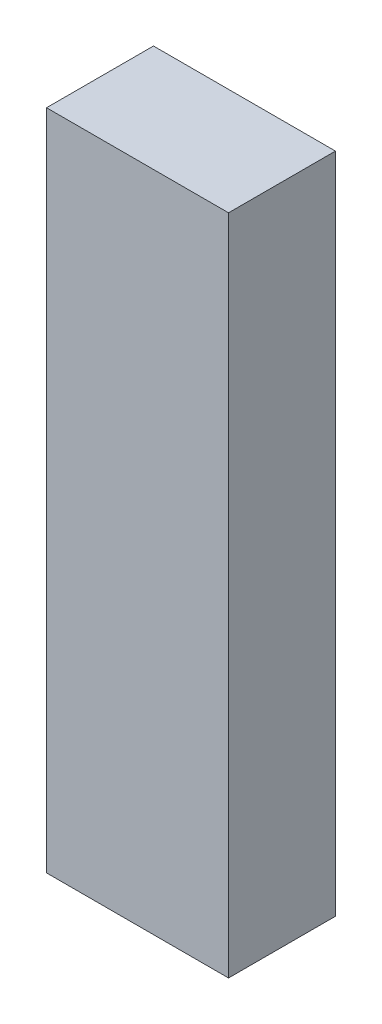
SolidWorks part; units mm, degrees
material "ABS"
ref_plane "Ground_Plane" through (0, 0, 0) normal (0, 0, 1) x (1, 0, 0)
ref_plane "VehicleCentre_Plane" through (0, 0, 0) normal (0, 1, 0) x (1, 0, 0)
ref_plane "FrontAxle_Plane" through (0, 0, 0) normal (1, 0, 0) x (0, 0, -1)
sketch "Sketch2" plane through (0, 0, 0) normal (1, 0, 0) x (0, 0, -1)
  line L1 (2.5, -15.495) -> (-2.5, -15.495)
  line L2 (2.5, -15.495) -> (2.5, 15.495)
  line L3 (2.5, 15.495) -> (-2.5, 15.495)
  line L4 (-2.5, -15.495) -> (-2.5, 15.495)
  line L5 (2.5, -15.495) -> (-2.5, 15.495) construction
  line L6 (2.5, 15.495) -> (-2.5, -15.495) construction
  point P0 (0, 0)
  dimension "D1" = 5
  dimension "D2" = 30.99
extrude "Boss-Extrude1" add sketch "Sketch2" along normal blind 8.51
sketch "Sketch3" plane through (0, 0, 0) normal (-1, 0, 0) x (0, 0, 1)
  line L0 (-2.5, -15.495) -> (-2.5, 15.495) construction
  line L1 (-1.5875, 14.2825) -> (-0.9525, 14.2825)
  line L2 (-1.5875, 14.2825) -> (-1.5875, 13.6475)
  line L3 (-1.5875, 13.6475) -> (-0.9525, 13.6475)
  line L4 (-0.9525, 14.2825) -> (-0.9525, 13.6475)
  line L5 (-1.5875, 14.2825) -> (-0.9525, 13.6475) construction
  line L6 (-1.5875, 13.6475) -> (-0.9525, 14.2825) construction
  line L7 (-2.5, 15.495) -> (2.5, 15.495) construction
  line L8 (0.9525, 14.2825) -> (0.9525, 13.6475)
  line L9 (0.9525, 14.2825) -> (1.5875, 14.2825)
  line L10 (1.5875, 14.2825) -> (1.5875, 13.6475)
  line L11 (0.9525, 13.6475) -> (1.5875, 13.6475)
  line L12 (0.9525, 11.7425) -> (0.9525, 11.1075)
  line L13 (0.9525, 11.7425) -> (1.5875, 11.7425)
  line L14 (1.5875, 11.7425) -> (1.5875, 11.1075)
  line L15 (0.9525, 11.1075) -> (1.5875, 11.1075)
  line L16 (0.9525, 9.2025) -> (0.9525, 8.5675)
  line L17 (0.9525, 9.2025) -> (1.5875, 9.2025)
  line L18 (1.5875, 9.2025) -> (1.5875, 8.5675)
  line L19 (0.9525, 8.5675) -> (1.5875, 8.5675)
  line L20 (0.9525, 6.6625) -> (0.9525, 6.0275)
  line L21 (0.9525, 6.6625) -> (1.5875, 6.6625)
  line L22 (1.5875, 6.6625) -> (1.5875, 6.0275)
  line L23 (0.9525, 6.0275) -> (1.5875, 6.0275)
  line L24 (0.9525, 4.1225) -> (0.9525, 3.4875)
  line L25 (0.9525, 4.1225) -> (1.5875, 4.1225)
  line L26 (1.5875, 4.1225) -> (1.5875, 3.4875)
  line L27 (0.9525, 3.4875) -> (1.5875, 3.4875)
  line L28 (0.9525, 1.5825) -> (0.9525, 0.9475)
  line L29 (0.9525, 1.5825) -> (1.5875, 1.5825)
  line L30 (1.5875, 1.5825) -> (1.5875, 0.9475)
  line L31 (0.9525, 0.9475) -> (1.5875, 0.9475)
  line L32 (0.9525, -0.9575) -> (0.9525, -1.5925)
  line L33 (0.9525, -0.9575) -> (1.5875, -0.9575)
  line L34 (1.5875, -0.9575) -> (1.5875, -1.5925)
  line L35 (0.9525, -1.5925) -> (1.5875, -1.5925)
  line L36 (0.9525, -3.4975) -> (0.9525, -4.1325)
  line L37 (0.9525, -3.4975) -> (1.5875, -3.4975)
  line L38 (1.5875, -3.4975) -> (1.5875, -4.1325)
  line L39 (0.9525, -4.1325) -> (1.5875, -4.1325)
  line L40 (0.9525, -6.0375) -> (0.9525, -6.6725)
  line L41 (0.9525, -6.0375) -> (1.5875, -6.0375)
  line L42 (1.5875, -6.0375) -> (1.5875, -6.6725)
  line L43 (0.9525, -6.6725) -> (1.5875, -6.6725)
  line L44 (0.9525, -8.5775) -> (0.9525, -9.2125)
  line L45 (0.9525, -8.5775) -> (1.5875, -8.5775)
  line L46 (1.5875, -8.5775) -> (1.5875, -9.2125)
  line L47 (0.9525, -9.2125) -> (1.5875, -9.2125)
  line L48 (0.9525, -11.1175) -> (0.9525, -11.7525)
  line L49 (0.9525, -11.1175) -> (1.5875, -11.1175)
  line L50 (1.5875, -11.1175) -> (1.5875, -11.7525)
  line L51 (0.9525, -11.7525) -> (1.5875, -11.7525)
  line L52 (0.9525, -13.6575) -> (0.9525, -14.2925)
  line L53 (0.9525, -13.6575) -> (1.5875, -13.6575)
  line L54 (1.5875, -13.6575) -> (1.5875, -14.2925)
  line L55 (0.9525, -14.2925) -> (1.5875, -14.2925)
  line L56 (-1.5875, 11.7425) -> (-1.5875, 11.1075)
  line L57 (-1.5875, 11.7425) -> (-0.9525, 11.7425)
  line L58 (-0.9525, 11.7425) -> (-0.9525, 11.1075)
  line L59 (-1.5875, 11.1075) -> (-0.9525, 11.1075)
  line L60 (-1.5875, 9.2025) -> (-1.5875, 8.5675)
  line L61 (-1.5875, 9.2025) -> (-0.9525, 9.2025)
  line L62 (-0.9525, 9.2025) -> (-0.9525, 8.5675)
  line L63 (-1.5875, 8.5675) -> (-0.9525, 8.5675)
  line L64 (-1.5875, 6.6625) -> (-1.5875, 6.0275)
  line L65 (-1.5875, 6.6625) -> (-0.9525, 6.6625)
  line L66 (-0.9525, 6.6625) -> (-0.9525, 6.0275)
  line L67 (-1.5875, 6.0275) -> (-0.9525, 6.0275)
  line L68 (-1.5875, 4.1225) -> (-1.5875, 3.4875)
  line L69 (-1.5875, 4.1225) -> (-0.9525, 4.1225)
  line L70 (-0.9525, 4.1225) -> (-0.9525, 3.4875)
  line L71 (-1.5875, 3.4875) -> (-0.9525, 3.4875)
  line L72 (-1.5875, 1.5825) -> (-1.5875, 0.9475)
  line L73 (-1.5875, 1.5825) -> (-0.9525, 1.5825)
  line L74 (-0.9525, 1.5825) -> (-0.9525, 0.9475)
  line L75 (-1.5875, 0.9475) -> (-0.9525, 0.9475)
  line L76 (-1.5875, -0.9575) -> (-1.5875, -1.5925)
  line L77 (-1.5875, -0.9575) -> (-0.9525, -0.9575)
  line L78 (-0.9525, -0.9575) -> (-0.9525, -1.5925)
  line L79 (-1.5875, -1.5925) -> (-0.9525, -1.5925)
  line L80 (-1.5875, -3.4975) -> (-1.5875, -4.1325)
  line L81 (-1.5875, -3.4975) -> (-0.9525, -3.4975)
  line L82 (-0.9525, -3.4975) -> (-0.9525, -4.1325)
  line L83 (-1.5875, -4.1325) -> (-0.9525, -4.1325)
  line L84 (-1.5875, -6.0375) -> (-1.5875, -6.6725)
  line L85 (-1.5875, -6.0375) -> (-0.9525, -6.0375)
  line L86 (-0.9525, -6.0375) -> (-0.9525, -6.6725)
  line L87 (-1.5875, -6.6725) -> (-0.9525, -6.6725)
  line L88 (-1.5875, -8.5775) -> (-1.5875, -9.2125)
  line L89 (-1.5875, -8.5775) -> (-0.9525, -8.5775)
  line L90 (-0.9525, -8.5775) -> (-0.9525, -9.2125)
  line L91 (-1.5875, -9.2125) -> (-0.9525, -9.2125)
  line L92 (-1.5875, -11.1175) -> (-1.5875, -11.7525)
  line L93 (-1.5875, -11.1175) -> (-0.9525, -11.1175)
  line L94 (-0.9525, -11.1175) -> (-0.9525, -11.7525)
  line L95 (-1.5875, -11.7525) -> (-0.9525, -11.7525)
  line L96 (-1.5875, -13.6575) -> (-1.5875, -14.2925)
  line L97 (-1.5875, -13.6575) -> (-0.9525, -13.6575)
  line L98 (-0.9525, -13.6575) -> (-0.9525, -14.2925)
  line L99 (-1.5875, -14.2925) -> (-0.9525, -14.2925)
  line L100 (-1.5875, 14.2825) -> (0.9525, 14.2825) construction
  line L101 (-1.5875, 14.2825) -> (-1.5875, 11.7425) construction
  point P0 (-1.27, 13.965)
  dimension "D1" = 0.635
  dimension "D2" = 1.23
  dimension "D3" = 1.53
  dimension "D6" = 2.54
  dimension "D7" = 2.54
  dimension "D4" = 2
  dimension "D5" = 12
extrude "Cut-Extrude1" cut sketch "Sketch3" against normal blind 4
chamfer "Chamfer2" distance 0.5 angle 45 96 edges at (0, 11.425, 0.9525) (0, 11.1075, 1.27) (0, 11.425, 1.5875) (0, 11.7425, 1.27) (0, 14.2825, 1.27) (0, 13.965, 1.5875) (0, 13.6475, 1.27) (0, 13.965, 0.9525) (0, 14.2825, -1.27) (0, 13.965, -1.5875) (0, 13.6475, -1.27) (0, 13.965, -0.9525) (0, 11.425, -0.9525) (0, 11.7425, -1.27) (0, 11.425, -1.5875) (0, 11.1075, -1.27) (0, 9.2025, -1.27) (0, 8.885, -1.5875) (0, 8.5675, -1.27) (0, 8.885, -0.9525) (0, 8.885, 1.5875) (0, 9.2025, 1.27) (0, 8.885, 0.9525) (0, 8.5675, 1.27) (0, 6.6625, 1.27) (0, 6.345, 1.5875) (0, 6.0275, 1.27) (0, 6.345, 0.9525) (0, 6.6625, -1.27) (0, 6.345, -1.5875) (0, 6.0275, -1.27) (0, 6.345, -0.9525) (0, 4.1225, -1.27) (0, 3.805, -1.5875) (0, 3.4875, -1.27) (0, 3.805, -0.9525) (0, 4.1225, 1.27) (0, 3.805, 0.9525) (0, 3.4875, 1.27) (0, 3.805, 1.5875) (0, 1.5825, 1.27) (0, 1.265, 1.5875) (0, 0.9475, 1.27) (0, 1.265, 0.9525) (0, 1.5825, -1.27) (0, 1.265, -1.5875) (0, 0.9475, -1.27) (0, 1.265, -0.9525) (0, -0.9575, -1.27) (0, -1.275, -0.9525) (0, -1.5925, -1.27) (0, -1.275, -1.5875) (0, -1.275, 0.9525) (0, -0.9575, 1.27) (0, -1.5925, 1.27) (0, -1.275, 1.5875) (0, -3.815, 1.5875) (0, -3.4975, 1.27) (0, -3.815, 0.9525) (0, -4.1325, 1.27) (0, -4.1325, -1.27) (0, -3.815, -1.5875) (0, -3.4975, -1.27) (0, -3.815, -0.9525) (0, -6.0375, 1.27) (0, -6.355, 1.5875) (0, -6.6725, 1.27) (0, -6.355, 0.9525) (0, -6.355, -1.5875) (0, -6.0375, -1.27) (0, -6.6725, -1.27) (0, -6.355, -0.9525) (0, -8.5775, -1.27) (0, -8.895, -1.5875) (0, -9.2125, -1.27) (0, -8.895, -0.9525) (0, -8.5775, 1.27) (0, -8.895, 0.9525) (0, -9.2125, 1.27) (0, -8.895, 1.5875) (0, -11.1175, 1.27) (0, -11.435, 1.5875) (0, -11.7525, 1.27) (0, -11.435, 0.9525) (0, -11.1175, -1.27) (0, -11.435, -0.9525) (0, -11.435, -1.5875) (0, -11.7525, -1.27) (0, -13.6575, 1.27) (0, -13.975, 1.5875) (0, -14.2925, 1.27) (0, -13.975, 0.9525) (0, -13.6575, -1.27) (0, -13.975, -1.5875) (0, -14.2925, -1.27) (0, -13.975, -0.9525)
